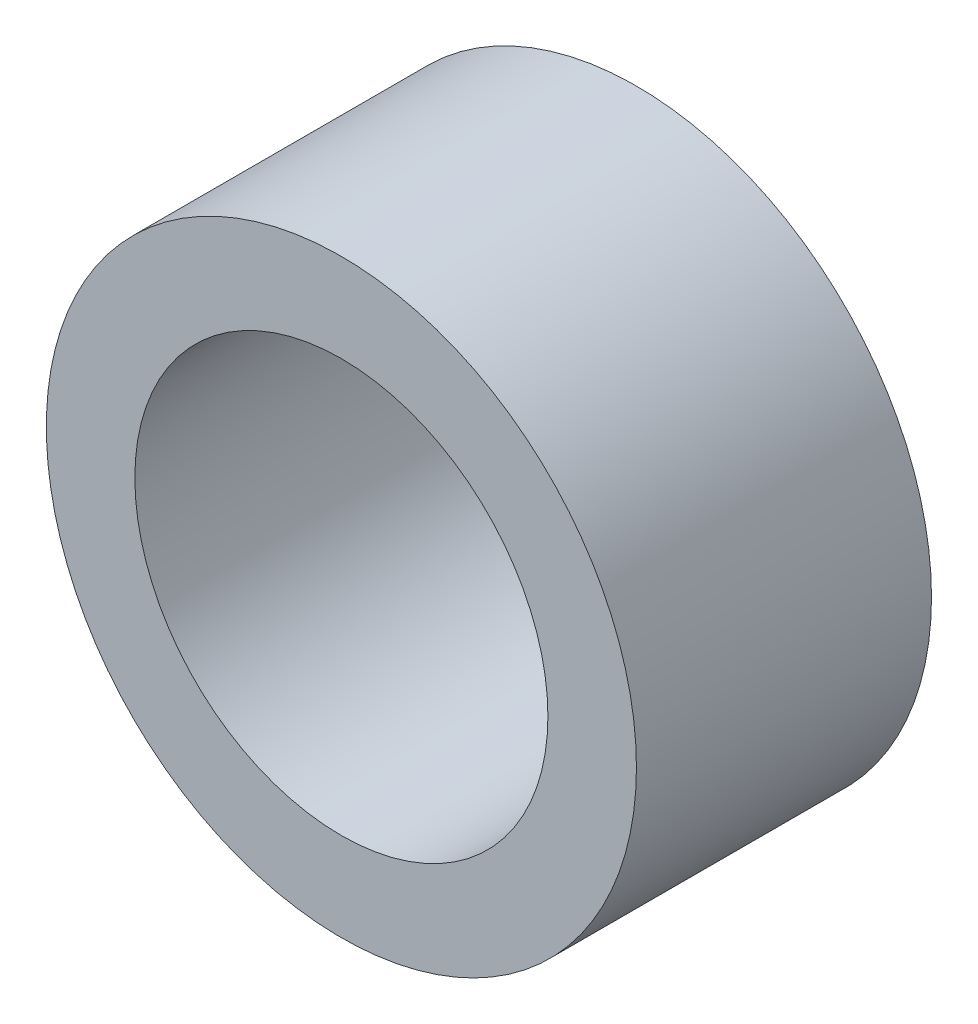
SolidWorks part; units mm, degrees
material "ABS"
ref_plane "前视基准面" through (0, 0, 0) normal (0, 0, 1) x (1, 0, 0)
ref_plane "上视基准面" through (0, 0, 0) normal (0, 1, 0) x (1, 0, 0)
ref_plane "右视基准面" through (0, 0, 0) normal (1, 0, 0) x (0, 0, -1)
sketch "草图1" plane through (0, 0, 0) normal (0, 0, 1) x (1, 0, 0)
  circle A0 centre (0, 0) radius 3
  circle A1 centre (0, 0) radius 2.1
  dimension "D1" = 4.2
  dimension "D2" = 6
extrude "凸台-拉伸1" add sketch "草图1" along normal blind 3
